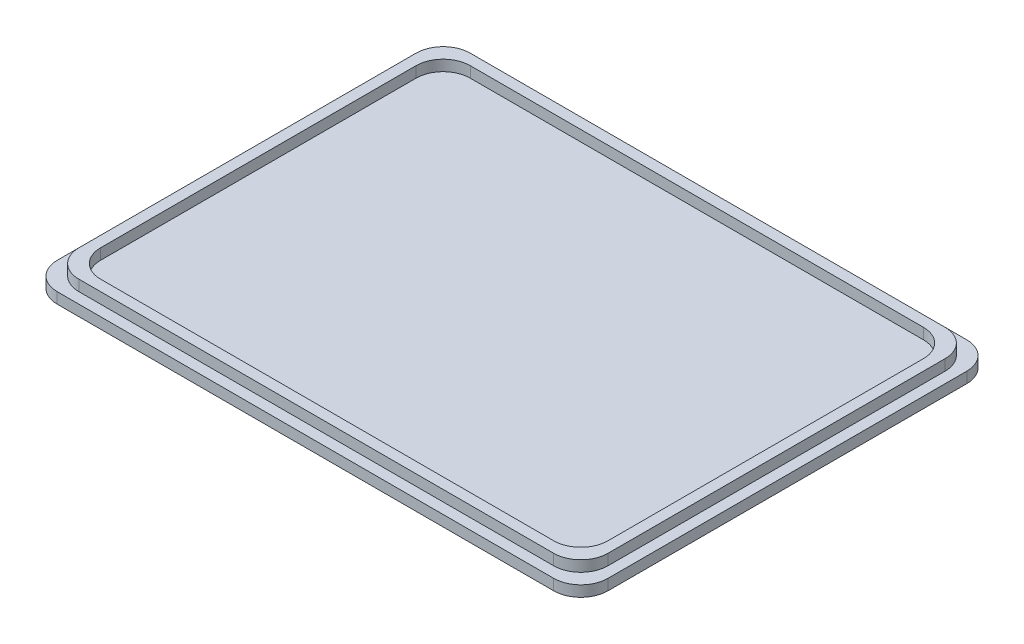
SolidWorks part; units mm, degrees
ref_plane "Front Plane" through (0, 0, 0) normal (0, 0, 1) x (1, 0, 0)
ref_plane "Top Plane" through (0, 0, 0) normal (0, 1, 0) x (1, 0, 0)
ref_plane "Right Plane" through (0, 0, 0) normal (1, 0, 0) x (0, 0, -1)
sketch "Sketch1" plane through (0, 0, 0) normal (0, 1, 0) x (1, 0, 0)
  line L1 (-50.8, -38.1) -> (50.8, -38.1)
  line L2 (-50.8, -38.1) -> (-50.8, 38.1)
  line L3 (-50.8, 38.1) -> (50.8, 38.1)
  line L4 (50.8, -38.1) -> (50.8, 38.1)
  line L5 (-50.8, -38.1) -> (50.8, 38.1) construction
  line L6 (-50.8, 38.1) -> (50.8, -38.1) construction
  point P0 (0, 0)
extrude "Boss-Extrude1" add sketch "Sketch1" along normal blind 2
sketch "Sketch2" plane through (0, 2, 0) normal (0, 1, 0) x (1, 0, 0)
  line L0 (-50.8, -38.1) -> (50.8, -38.1) construction
  line L1 (50.8, -38.1) -> (50.8, 38.1) construction
  line L2 (50.8, 38.1) -> (-50.8, 38.1) construction
  line L3 (-50.8, 38.1) -> (-50.8, -38.1) construction
  line L4 (-48.8, 36.1) -> (-48.8, -36.1)
  line L5 (-48.8, -36.1) -> (48.8, -36.1)
  line L6 (48.8, -36.1) -> (48.8, 36.1)
  line L7 (48.8, 36.1) -> (-48.8, 36.1)
  line L8 (-46.8, 34.1) -> (-46.8, -34.1)
  line L9 (-46.8, -34.1) -> (46.8, -34.1)
  line L10 (46.8, -34.1) -> (46.8, 34.1)
  line L11 (46.8, 34.1) -> (-46.8, 34.1)
  dimension "D1" = 2
  dimension "D2" = 2
extrude "Extrude-Thin1" add sketch "Sketch2" along normal blind 2 thin contours L4 L5 L6 L7
fillet "Fillet1" radius 5 4 edges at (-50.8, 1, -38.1) (-50.8, 1, 38.1) (50.8, 1, -38.1) (50.8, 1, 38.1)
fillet "Fillet2" radius 5 8 edges at (46.8, 3, -34.1) (46.8, 3, 34.1) (-46.8, 3, 34.1) (-46.8, 3, -34.1) (48.8, 3, -36.1) (48.8, 3, 36.1) (-48.8, 3, 36.1) (-48.8, 3, -36.1)
